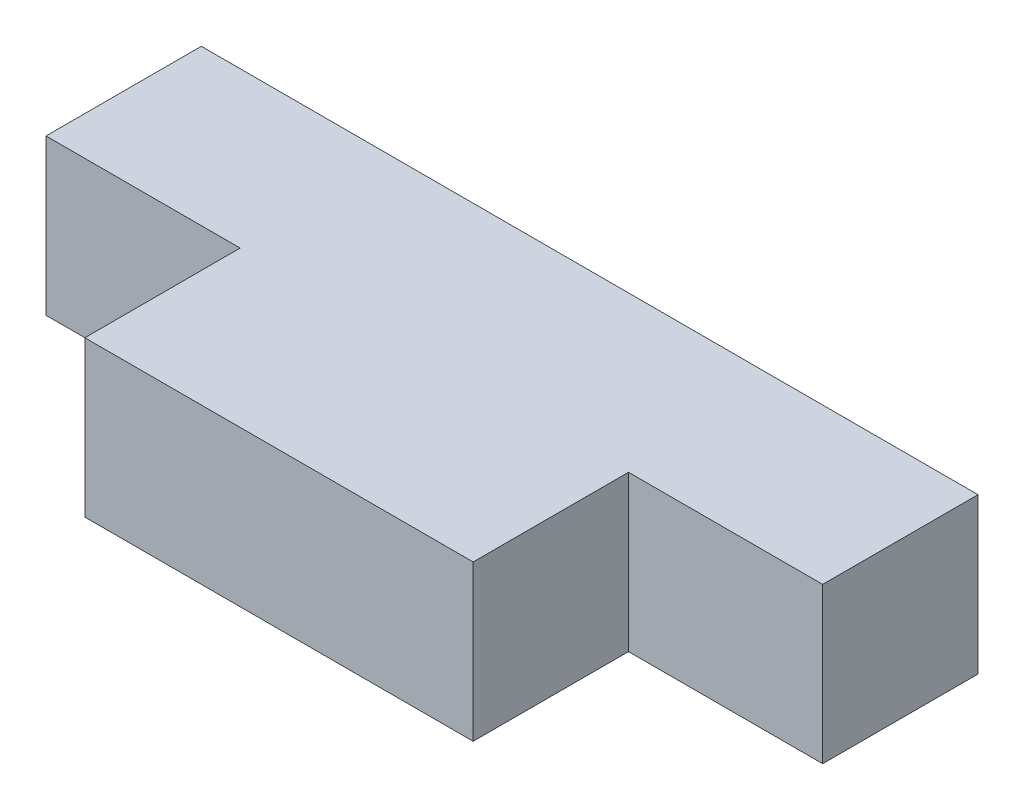
SolidWorks part; units mm, degrees
ref_plane "Front Plane" through (0, 0, 0) normal (0, 0, 1) x (1, 0, 0)
ref_plane "Top Plane" through (0, 0, 0) normal (0, 1, 0) x (1, 0, 0)
ref_plane "Right Plane" through (0, 0, 0) normal (1, 0, 0) x (0, 0, -1)
sketch "Sketch1" plane through (0, 0, 0) normal (0, 1, 0) x (1, 0, 0)
  line L0 (-37.6456, 14.8071) -> (-37.6456, 8.8071)
  line L1 (-45.1456, 20.8071) -> (-15.1456, 20.8071)
  line L2 (-45.1456, 20.8071) -> (-45.1456, 14.8071)
  line L3 (-45.1456, 14.8071) -> (-37.6456, 14.8071)
  line L4 (-15.1456, 20.8071) -> (-15.1456, 14.8071)
  line L5 (-37.6456, 8.8071) -> (-22.6456, 8.8071)
  line L6 (-22.6456, 8.8071) -> (-22.6456, 14.8071)
  line L7 (-22.6456, 14.8071) -> (-15.1456, 14.8071)
  dimension "D1" = 30
  dimension "D2" = 6
  dimension "D3" = 15
  dimension "D4" = 7.5
  dimension "D5" = 6
extrude "Boss-Extrude1" add sketch "Sketch1" along normal blind 6
